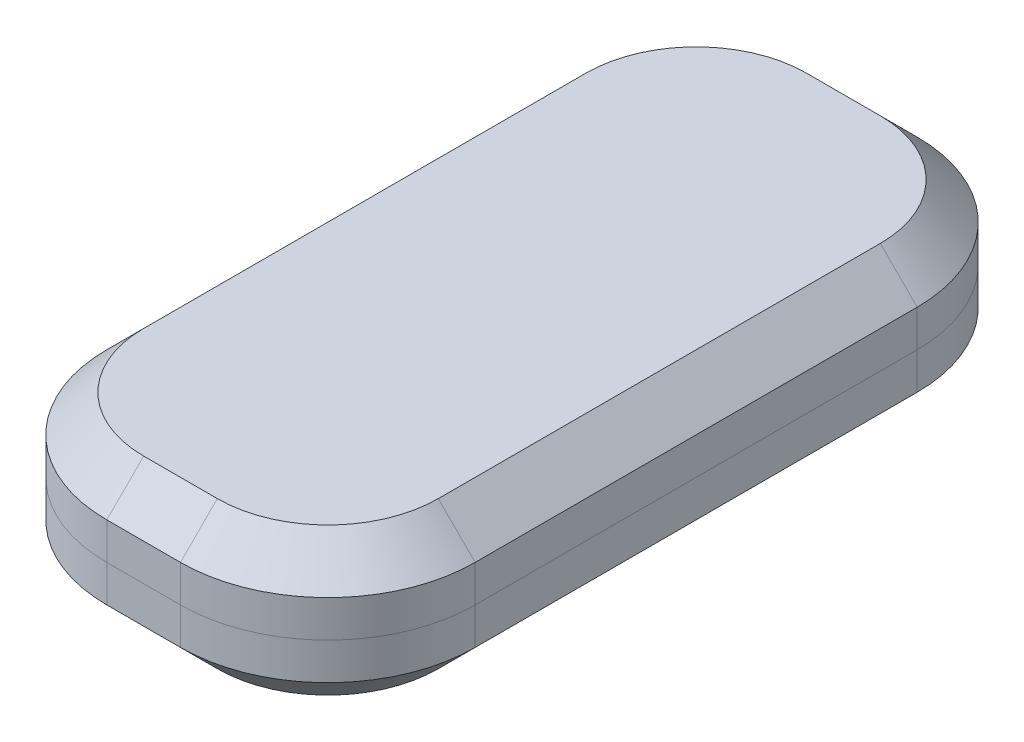
SolidWorks part; units mm, degrees
ref_plane "Front Plane" through (0, 0, 0) normal (0, 0, 1) x (1, 0, 0)
ref_plane "Top Plane" through (0, 0, 0) normal (0, 1, 0) x (1, 0, 0)
ref_plane "Right Plane" through (0, 0, 0) normal (1, 0, 0) x (0, 0, -1)
sketch "Sketch1" plane through (0, 0, 0) normal (0, 1, 0) x (1, 0, 0)
  line L1 (-5, -50) -> (5, -50)
  line L2 (-25, -30) -> (-25, 30)
  line L3 (-5, 50) -> (5, 50)
  line L4 (25, -30) -> (25, 30)
  line L5 (-25, -50) -> (25, 50) construction
  line L6 (-25, 50) -> (25, -50) construction
  arc A0 (-5, -50) -> (-25, -30) centre (-5, -30) cw
  arc A1 (5, -50) -> (25, -30) centre (5, -30) ccw
  arc A2 (5, 50) -> (25, 30) centre (5, 30) cw
  arc A3 (-25, 30) -> (-5, 50) centre (-5, 30) cw
  point P0 (0, 0)
  dimension "D3" = 20
  dimension "D1" = 100
  dimension "D2" = 50
extrude "Boss-Extrude1" add sketch "Sketch1" along normal blind 20
chamfer "Chamfer1" distance 5 angle 45 16 edges at (0, 0, 50) (19.1421, 0, 44.1421) (25, 0, 0) (19.1421, 0, -44.1421) (0, 0, -50) (-19.1421, 0, -44.1421) (-25, 0, 0) (-19.1421, 0, 44.1421) (-25, 20, 0) (-19.1421, 20, -44.1421) (0, 20, -50) (19.1421, 20, -44.1421) (25, 20, 0) (19.1421, 20, 44.1421) (0, 20, 50) (-19.1421, 20, 44.1421)
ref_plane "Plane1" through (0, 10, 0) normal (0, 1, 0) x (1, 0, 0)
split "Split1" trim tools "Plane1" bodies to split 101 resulting bodies 102 103
shell "Shell1" thickness 2
shell "Shell2" thickness 2
sketch "Sketch2" plane through (0, 10, 0) normal (0, 1, 0) x (1, 0, 0)
  line L8 (-22.5, 30) -> (-22.5, -30)
  line L9 (5, 47.5) -> (-5, 47.5)
  line L10 (22.5, -30) -> (22.5, 30)
  line L11 (-5, -47.5) -> (5, -47.5)
  line L12 (-22.5, 30) -> (-22.5, -30)
  line L13 (5, 47.5) -> (-5, 47.5)
  line L14 (22.5, -30) -> (22.5, 30)
  line L15 (-5, -47.5) -> (5, -47.5)
  arc A8 (-5, 47.5) -> (-22.5, 30) centre (-5, 30) ccw
  arc A9 (22.5, 30) -> (5, 47.5) centre (5, 30) ccw
  arc A10 (5, -47.5) -> (22.5, -30) centre (5, -30) ccw
  arc A11 (-22.5, -30) -> (-5, -47.5) centre (-5, -30) ccw
  arc A12 (-5, 47.5) -> (-22.5, 30) centre (-5, 30) ccw
  arc A13 (22.5, 30) -> (5, 47.5) centre (5, 30) ccw
  arc A14 (5, -47.5) -> (22.5, -30) centre (5, -30) ccw
  arc A15 (-22.5, -30) -> (-5, -47.5) centre (-5, -30) ccw
  dimension "D1" = 2.5
